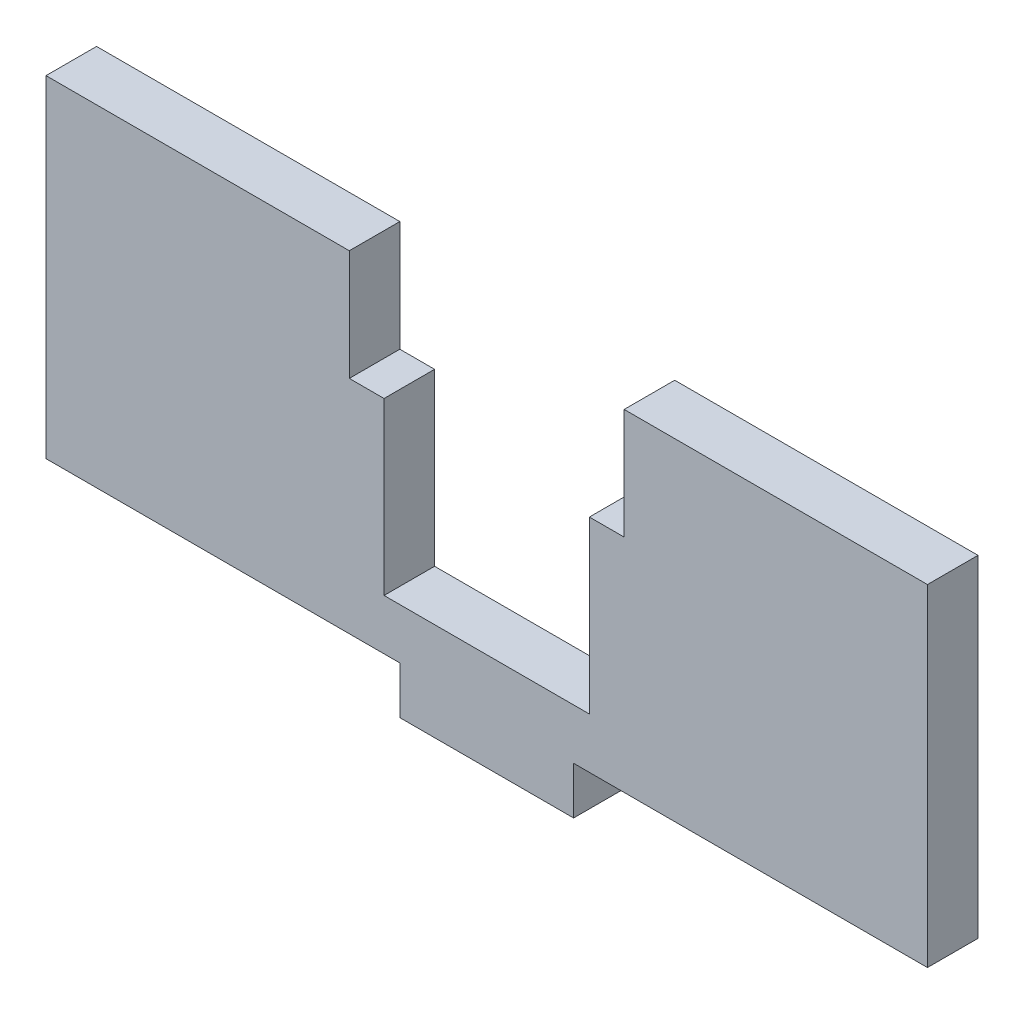
SolidWorks part; units mm, degrees
ref_plane "Front Plane" through (0, 0, 0) normal (0, 0, 1) x (1, 0, 0)
ref_plane "Top Plane" through (0, 0, 0) normal (0, 1, 0) x (1, 0, 0)
ref_plane "Right Plane" through (0, 0, 0) normal (1, 0, 0) x (0, 0, -1)
sketch "Sketch1" plane through (0, 0, 0) normal (0, 0, 1) x (1, 0, 0)
  line L0 (2.75, 0) -> (-2.75, 0)
  line L1 (-2.75, 0) -> (-2.75, 1.5)
  line L2 (-2.75, 1.5) -> (-13.95, 1.5)
  line L3 (-13.95, 1.5) -> (-13.95, 11)
  line L4 (-13.95, 11) -> (-4.35, 11)
  line L5 (-4.35, 11) -> (-4.35, 9.5)
  line L6 (-3.25, 3.1) -> (3.25, 3.1)
  line L7 (0, 0) -> (0, 3.1) construction
  line L8 (-4.35, 9.5) -> (-3.25, 9.5)
  line L9 (-3.25, 9.5) -> (-3.25, 3.1)
  line L10 (3.25, 9.5) -> (3.25, 3.1)
  line L11 (4.35, 9.5) -> (3.25, 9.5)
  line L12 (4.35, 11) -> (4.35, 9.5)
  line L13 (13.95, 11) -> (4.35, 11)
  line L14 (13.95, 1.5) -> (13.95, 11)
  line L15 (2.75, 1.5) -> (13.95, 1.5)
  line L16 (2.75, 0) -> (2.75, 1.5)
  dimension "D1" = 9.6
  dimension "D2" = 8.7
  dimension "D3" = 6.5
  dimension "D4" = 9.5
  dimension "D5" = 1.5
  dimension "D6" = 1.5
  dimension "D7" = 6.4
  dimension "D8" = 1.6
  dimension "D9" = 5.5
extrude "Boss-Extrude1" add sketch "Sketch1" along normal blind 1.6
sketch "Sketch2" plane through (0, 0, 1.6) normal (0, 0, 1) x (1, 0, 0)
  line L0 (4.35, 11) -> (4.35, 9.5) construction
  line L1 (-4.35, 9.5) -> (4.35, 9.5)
  line L2 (-4.35, 9.5) -> (-4.35, 8.5)
  line L3 (-4.35, 8.5) -> (4.35, 8.5)
  line L4 (4.35, 9.5) -> (4.35, 8.5)
  line L5 (4.35, 9.5) -> (3.25, 9.5) construction
  point P4 (4.35, 9.5)
  dimension "D1" = 1
extrude "Cut-Extrude1" cut sketch "Sketch2" against normal blind 1.6
sketch "Sketch3" plane through (0, 0, 1.6) normal (0, 0, 1) x (1, 0, 0)
  line L0 (-4.35, 8.5) -> (-4.35, 11) construction
  line L1 (-13.95, 11) -> (-4.35, 11)
  line L2 (-13.95, 11) -> (-13.95, 12)
  line L3 (-13.95, 12) -> (-4.35, 12)
  line L4 (-4.35, 11) -> (-4.35, 12)
  line L5 (13.95, 11) -> (4.35, 11)
  line L6 (13.95, 11) -> (13.95, 12)
  line L7 (13.95, 12) -> (4.35, 12)
  line L8 (4.35, 11) -> (4.35, 12)
  line L9 (4.35, 11) -> (4.35, 8.5) construction
  point P9 (-4.35, 11)
  point P13 (4.35, 11)
  dimension "D1" = 1
extrude "Boss-Extrude2" add sketch "Sketch3" against normal up to surface (1.6 mm away) up to face at (0, 5.6375, 0)
